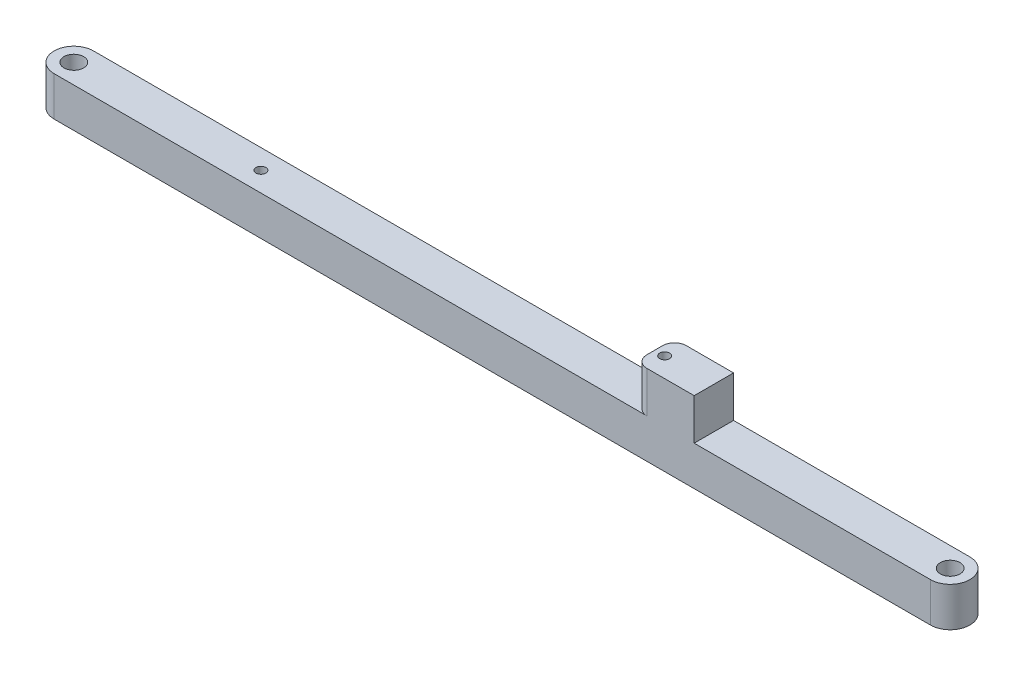
SolidWorks part; units mm, degrees
ref_plane "Front Plane" through (0, 0, 0) normal (0, 0, 1) x (1, 0, 0)
ref_plane "Top Plane" through (0, 0, 0) normal (0, 1, 0) x (1, 0, 0)
ref_plane "Right Plane" through (0, 0, 0) normal (1, 0, 0) x (0, 0, -1)
sketch "Sketch2" plane through (0, 0, 0) normal (0, 1, 0) x (1, 0, 0)
  line L0 (0, 0) -> (120.65, 0)
  line L1 (0, 0) -> (565.15, 0)
  line L2 (0, 0) -> (0, 25.4) construction
  line L3 (0, 25.4) -> (565.15, 25.4)
  line L4 (565.15, 0) -> (565.15, 25.4) construction
  line L5 (120.65, 0) -> (120.65, 25.4) construction
  circle A0 centre (120.65, 12.7) radius 12.7
  arc A1 (565.15, 25.4) -> (565.15, 0) centre (565.15, 12.7) cw
  circle A2 centre (120.65, 12.7) radius 3.175
  circle A3 centre (565.15, 12.7) radius 6.35
  arc A4 (0, 25.4) -> (0, 0) centre (0, 12.7) ccw
  circle A5 centre (0, 12.7) radius 6.35
  dimension "D4" = 6.35
  dimension "D5" = 12.7
  dimension "D6" = 12.7
  dimension "D1" = 565.15
  dimension "D2" = 25.4
  dimension "D3" = 120.65
extrude "Boss-Extrude1" add sketch "Sketch2" along normal blind 25.4 contours A0 L3 L2 L0 | A0 A2 | A1 L3 A0 L1 A3
sketch "Sketch14" plane through (0, 25.4, 0) normal (0, 1, 0) x (1, 0, 0)
  line L0 (565.15, 25.4) -> (374.65, 25.4) construction
  line L2 (0, 0) -> (565.15, 0) construction
  line L3 (374.65, 0) -> (412.75, 0)
  line L4 (0, 25.4) -> (565.15, 25.4) construction
  line L6 (412.75, 0) -> (412.75, 25.4)
  line L7 (374.65, 0) -> (374.65, 25.4)
  line L8 (374.65, 25.4) -> (412.75, 25.4)
  dimension "D1" = 190.5
  dimension "D2" = 38.1
extrude "Boss-Extrude2" add sketch "Sketch14" along normal blind 26.543
sketch "Sketch15" plane through (0, 51.943, 0) normal (0, 1, 0) x (1, 0, 0)
  line L0 (374.65, 12.7) -> (381, 12.7) construction
  line L1 (374.65, 25.4) -> (374.65, 0) construction
  circle A0 centre (381, 12.7) radius 3.175
  dimension "D2" = 6.35
  dimension "D1" = 6.35
extrude "Cut-Extrude1" cut sketch "Sketch15" against normal blind 19.05
fillet "Fillet1" radius 7.62 2 edges
